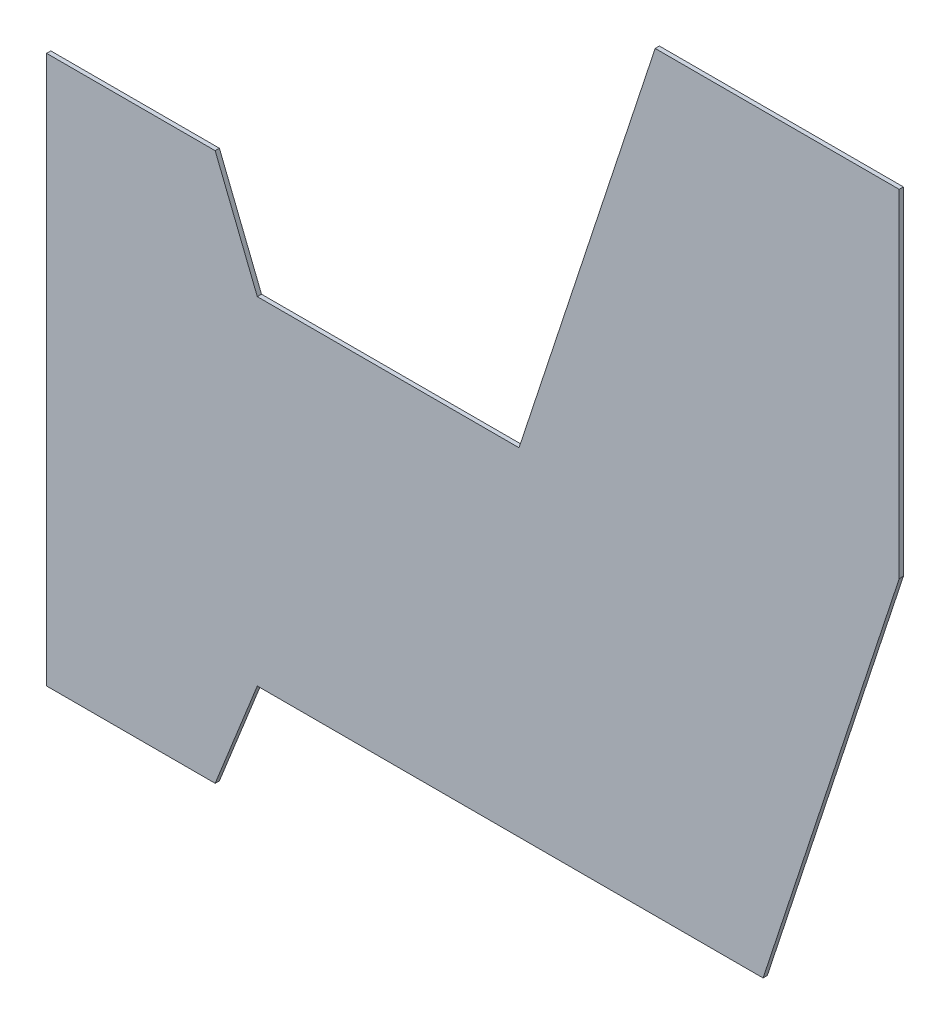
SolidWorks part; units mm, degrees
ref_plane "Front Plane" through (0, 0, 0) normal (0, 0, 1) x (1, 0, 0)
ref_plane "Top Plane" through (0, 0, 0) normal (0, 1, 0) x (1, 0, 0)
ref_plane "Right Plane" through (0, 0, 0) normal (1, 0, 0) x (0, 0, -1)
sketch "Sketch1" plane through (0, 0, 0) normal (0, 0, 1) x (1, 0, 0)
  line L2 (0, 0) -> (0, 330.2)
  line L5 (0, 0) -> (101.6, 0)
  line L6 (0, 330.2) -> (101.6, 330.2)
  line L8 (101.6, 0) -> (127, 63.5)
  line L9 (101.6, 330.2) -> (127, 266.7)
  line L10 (127, 63.5) -> (431.8, 63.5)
  line L14 (127, 266.7) -> (284.7259, 266.7)
  line L17 (431.8, 63.5) -> (513.8402, 312.928)
  line L19 (366.7661, 516.128) -> (513.8402, 516.128)
  line L20 (284.7259, 266.7) -> (366.7661, 516.128)
  line L21 (513.8402, 516.128) -> (513.8402, 312.928)
  dimension "D1" = 25.4
  dimension "D2" = 68.3916
  dimension "D3" = 330.2
  dimension "D4" = 101.6
  dimension "D5" = 101.6
  dimension "D6" = 68.3916
  dimension "D7" = 25.4
  dimension "D8" = 203.2
  dimension "D9" = 452.628
  dimension "D10" = 513.8402
  dimension "D11" = 304.8
  dimension "D12" = 203.2
extrude "Boss-Extrude1" add sketch "Sketch1" along normal blind 2.54
